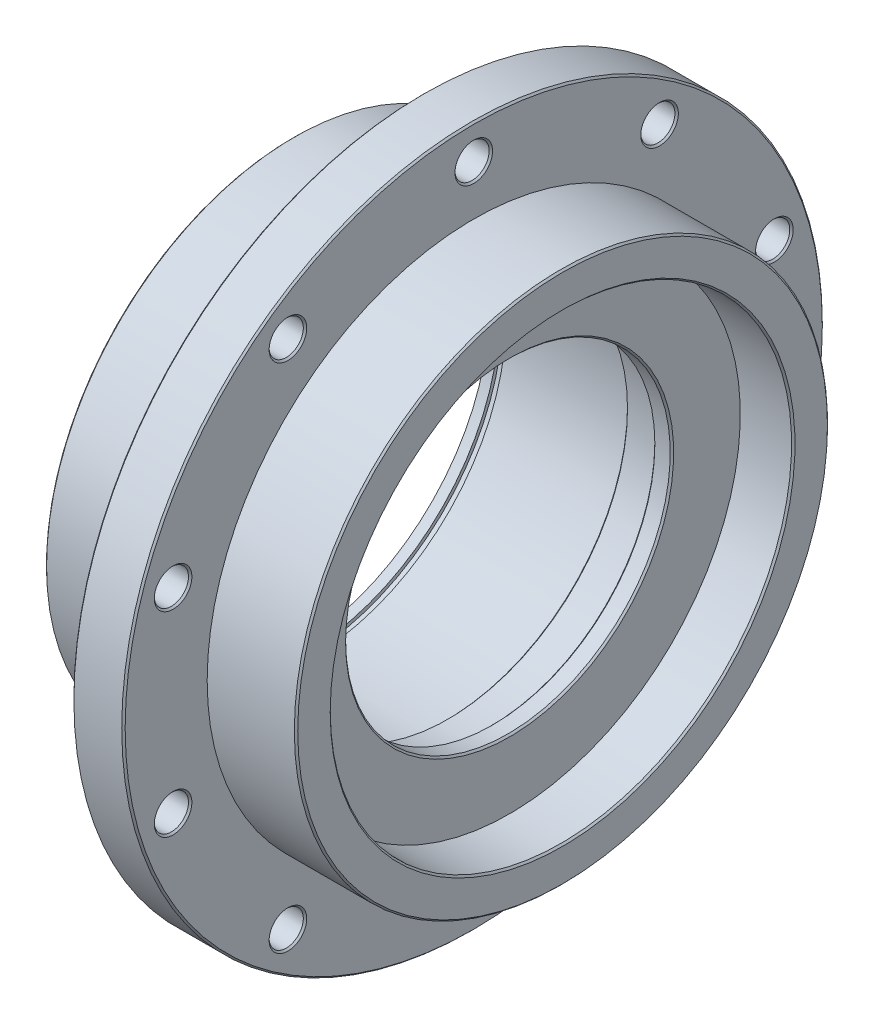
SolidWorks part; units mm, degrees
ref_plane "前视基准面" through (0, 0, 0) normal (0, 0, 1) x (1, 0, 0)
ref_plane "上视基准面" through (0, 0, 0) normal (0, 1, 0) x (1, 0, 0)
ref_plane "右视基准面" through (0, 0, 0) normal (1, 0, 0) x (0, 0, -1)
other "Configuration Table"
sketch "草图1" plane through (0, 0, 0) normal (0, 0, 1) x (1, 0, 0)
  line L0 (0, 0) -> (248.0835, 0) construction
  line L1 (0, 57.5) -> (0, 72.5)
  line L2 (0, 72.5) -> (38, 72.5)
  line L3 (38, 72.5) -> (38, 102.5)
  line L4 (38, 102.5) -> (53, 102.5)
  line L5 (53, 102.5) -> (53, 78)
  line L6 (53, 78) -> (79, 78)
  line L7 (79, 78) -> (79, 67.5)
  line L8 (79, 67.5) -> (63.5, 67.5)
  line L9 (63.5, 67.5) -> (63.5, 47.5)
  line L10 (63.5, 47.5) -> (58, 47.5)
  line L11 (58, 47.5) -> (58, 52.5)
  line L12 (58, 52.5) -> (45, 52.5)
  line L13 (45, 52.5) -> (45, 57.5)
  line L16 (45, 57.5) -> (5, 57.5)
  line L17 (5, 57.5) -> (5, 58.5)
  line L18 (5, 58.5) -> (3, 58.5)
  line L19 (3, 58.5) -> (3, 57.5)
  line L20 (3, 57.5) -> (0, 57.5)
  dimension "D1" = 115
  dimension "D2" = 117
  dimension "D3" = 145
  dimension "D4" = 205
  dimension "D5" = 156
  dimension "D6" = 135
  dimension "D7" = 95
  dimension "D8" = 3
  dimension "D9" = 2
  dimension "D10" = 45
  dimension "D11" = 58
  dimension "D12" = 15.5
  dimension "D13" = 63.5
  dimension "D14" = 38
  dimension "D15" = 26
  dimension "D16" = 105
revolve "旋转1" add sketch "草图1" angle 360 about L0
sketch "草图3" plane through (38, 0, 0) normal (-1, 0, 0) x (0, 0, 1)
  circle A0 centre (0, 0) radius 92.5 construction
  circle A1 centre (0, 92.5) radius 5
  circle A2 centre (54.3701, 74.8341) radius 5
  circle A3 centre (87.9727, 28.5841) radius 5
  circle A4 centre (87.9727, -28.5841) radius 5
  circle A5 centre (54.3701, -74.8341) radius 5
  circle A6 centre (0, -92.5) radius 5
  circle A7 centre (-54.3701, -74.8341) radius 5
  circle A8 centre (-87.9727, -28.5841) radius 5
  circle A9 centre (-87.9727, 28.5841) radius 5
  circle A10 centre (-54.3701, 74.8341) radius 5
  point P6 (110.9214, -32.4445)
  point P7 (0, 0)
  point P25 (0, 0)
  dimension "D1" = 185
  dimension "D2" = 10
  dimension "D3" = 10
extrude "切除-拉伸2" cut sketch "草图3" against normal through all
sketch "草图4" plane through (0, 0, 0) normal (-1, 0, 0) x (0, 0, 1)
  line L0 (0, 0) -> (0, 65) construction
  circle A0 centre (0, 0) radius 65 construction
  dimension "D1" = 130
hole_wizard "Ø5.0 (5) 直径孔1" positions "3D草图1" profile "草图5" hole size "Ø5.0" standard "GB"
sketch3d "3D草图1"
  point P0 (0, 65, 0)
sketch "草图5" plane through (0, 65, 0) normal (0, 1, 0) x (0, 0, 1)
  line L0 (0, 0) -> (0, 16.5022)
  line L1 (0, 16.5022) -> (2.5, 15)
  line L2 (2.5, 15) -> (2.5, 0)
  line L5 (2.5, 0) -> (0, 0)
  line L10 (0, 16.5022) -> (-2.5, 15) construction
  line L11 (0, -6.35) -> (0, 107.95) construction
  dimension "孔直径" = 5
  dimension "孔深度" = 15
  dimension "导头角度" = 118
pattern_circular "阵列(圆周)1" count 4 over 360 about axis through (0, 0, 0) along (1, 0, 0) of "Ø5.0 (5) 直径孔1"
chamfer "倒角1" distance 0.5 angle 45 8 edges at (0, 0, 72.5) (38, 0, 102.5) (53, 0, 102.5) (79, 0, 78) (45, 0, 52.5) (58, 0, 47.5) (63.5, 0, 47.5) (79, 0, 67.5)
chamfer "倒角2" distance 0.5 angle 45 24 edges at (0, -65, 2.5) (0, 0, 67.5) (0, 65, 2.5) (0, 0, -62.5) (53, 74.8341, 59.3701) (53, 28.5841, 92.9727) (53, -28.5841, 92.9727) (53, -74.8341, 59.3701) (53, -92.5, 5) (53, -74.8341, -49.3701) (53, -28.5841, -82.9727) (53, 28.5841, -82.9727) (53, 74.8341, -49.3701) (53, 92.5, 5) (38, 92.5, 5) (38, 74.8341, 59.3701) (38, 28.5841, 92.9727) (38, -28.5841, 92.9727) (38, -74.8341, 59.3701) (38, -92.5, 5) (38, -74.8341, -49.3701) (38, -28.5841, -82.9727) (38, 28.5841, -82.9727) (38, 74.8341, -49.3701)
